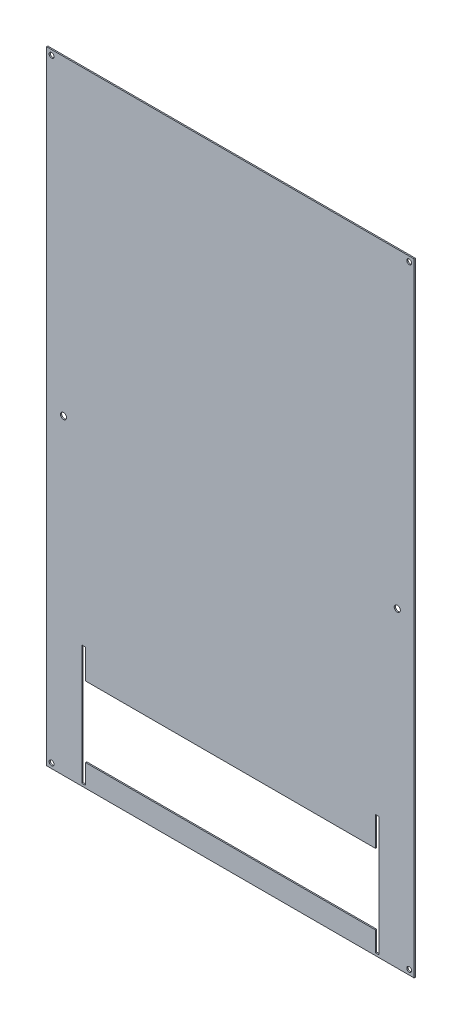
SolidWorks part; units mm, degrees
ref_plane "Front Plane" through (0, 0, 0) normal (0, 0, 1) x (1, 0, 0)
ref_plane "Top Plane" through (0, 0, 0) normal (0, 1, 0) x (1, 0, 0)
ref_plane "Right Plane" through (0, 0, 0) normal (1, 0, 0) x (0, 0, -1)
sketch "Sketch2" plane through (0, 0, 0) normal (0, 0, 1) x (1, 0, 0)
  line L0 (108.8476, 918.9814) -> (-369.1524, 918.9814)
  line L1 (109.8476, 919.9814) -> (-370.1524, 919.9814) construction
  line L2 (109.8476, 919.9814) -> (109.8476, 108.0813) construction
  line L3 (109.8476, 108.0813) -> (-370.1524, 108.0813) construction
  line L4 (-370.1524, 919.9814) -> (-370.1524, 108.0813) construction
  line L5 (-369.1524, 918.9814) -> (-369.1524, 109.0813)
  line L6 (108.8476, 109.0813) -> (-369.1524, 109.0813)
  line L7 (108.8476, 918.9814) -> (108.8476, 109.0813)
  line L8 (63.1114, 112.3589) -> (63.1114, 229.8981)
  line L9 (-323.43, 229.8981) -> (-323.43, 268.0814)
  line L10 (-323.43, 229.8981) -> (-323.43, 112.3589)
  line L11 (-323.43, 112.3589) -> (-318.6675, 112.3589)
  line L12 (-318.6675, 112.3589) -> (-318.6675, 138.0814)
  line L13 (-318.6675, 138.0814) -> (58.3489, 138.0814)
  line L14 (58.3489, 138.0814) -> (58.3489, 112.3589)
  line L15 (58.3489, 112.3589) -> (63.1114, 112.3589)
  line L16 (-323.43, 268.0814) -> (-318.6675, 268.0814)
  line L17 (-318.6675, 229.8981) -> (58.3489, 229.8981)
  line L18 (58.3489, 229.8981) -> (58.3489, 268.0814)
  line L19 (58.3489, 268.0814) -> (63.1114, 268.0814)
  line L20 (-318.6675, 229.8981) -> (-318.6675, 268.0814)
  line L21 (63.1114, 229.8981) -> (63.1114, 268.0814)
  circle A0 centre (-362.7102, 115.5224) radius 3.175 construction
  circle A1 centre (-362.7102, 115.5224) radius 3.175
  circle A2 centre (102.4054, 912.5404) radius 3.175 construction
  circle A3 centre (-362.7102, 912.5404) radius 3.175 construction
  circle A4 centre (102.4054, 115.5224) radius 3.175 construction
  circle A5 centre (102.4054, 912.5404) radius 3.175
  circle A6 centre (-362.7102, 912.5404) radius 3.175
  circle A7 centre (102.4054, 115.5224) radius 3.175
  circle A8 centre (86.8936, 514.0313) radius 3.9687 construction
  circle A9 centre (-347.1984, 514.0313) radius 3.9687 construction
  circle A10 centre (86.8936, 514.0313) radius 3.9687
  circle A11 centre (-347.1984, 514.0313) radius 3.9687
extrude "Boss-Extrude1" add sketch "Sketch2" along normal blind 1.6002
